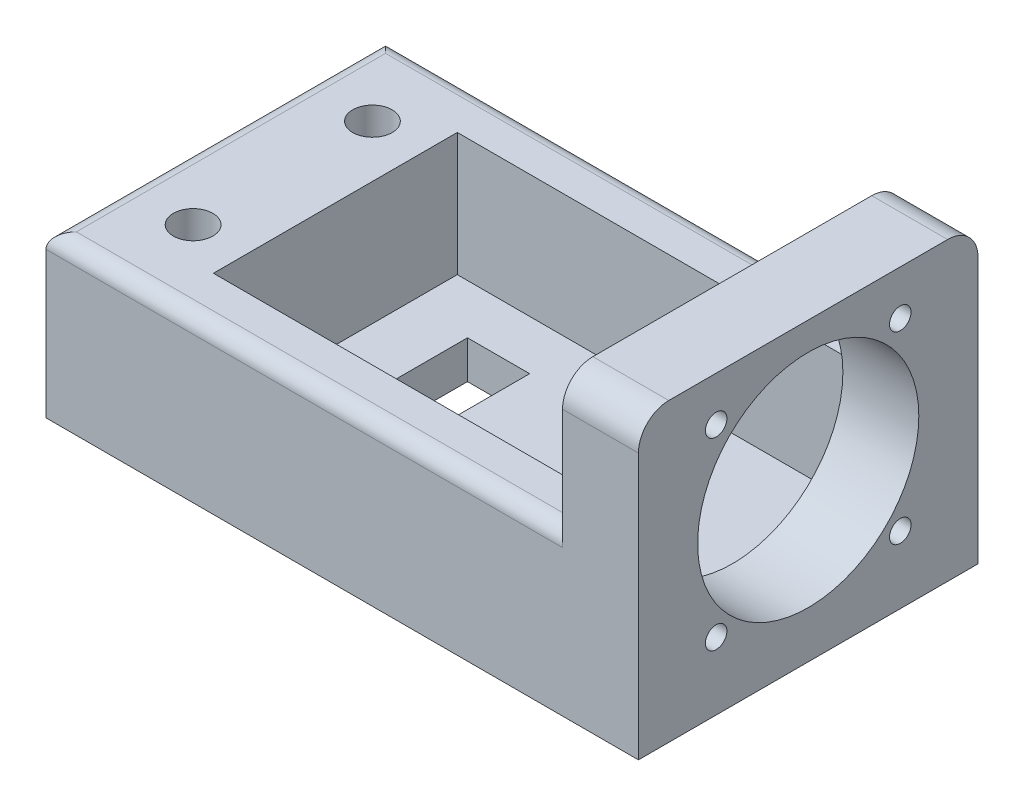
SolidWorks part; units mm, degrees
material "ABS PC"
ref_plane "Front Plane" through (0, 0, 0) normal (0, 0, 1) x (1, 0, 0)
ref_plane "Top Plane" through (0, 0, 0) normal (0, 1, 0) x (1, 0, 0)
ref_plane "Right Plane" through (0, 0, 0) normal (1, 0, 0) x (0, 0, -1)
sketch "Sketch1" plane through (0, 0, 0) normal (0, 1, 0) x (1, 0, 0)
  line L1 (0, 0) -> (43.2003, 0)
  line L2 (0, 0) -> (0, 28.3997)
  line L3 (0, 28.3997) -> (43.2003, 28.3997)
  line L4 (43.2003, 0) -> (43.2003, 28.3997)
  dimension "D1" = 28.3997
  dimension "D2" = 43.2003
extrude "Boss-Extrude1" add sketch "Sketch1" along normal blind 13.4747
sketch "Sketch2" plane through (0, 13.4747, 0) normal (0, 1, 0) x (1, 0, 0)
  line L0 (43.2003, 0) -> (43.2003, 28.3997) construction
  line L1 (43.2003, 24.3992) -> (10, 24.3992)
  line L2 (43.2003, 24.3992) -> (43.2003, 4.0005)
  line L3 (43.2003, 4.0005) -> (10, 4.0005)
  line L4 (10, 24.3992) -> (10, 4.0005)
  line L5 (0, 28.3997) -> (0, 0) construction
  line L6 (0, 0) -> (43.2003, 0) construction
  dimension "D1" = 10
  dimension "D2" = 20.3987
  dimension "D3" = 4.0005
extrude "Cut-Extrude1" cut sketch "Sketch2" against normal blind 10.2997
sketch "Sketch3" plane through (0, 3.175, 0) normal (0, 1, 0) x (1, 0, 0)
  line L1 (15.0012, 20.2502) -> (20.2006, 20.2501)
  line L2 (15.0012, 20.2502) -> (15.0012, 8.1496)
  line L3 (15.0012, 8.1496) -> (20.2006, 8.1496)
  line L4 (20.2006, 20.2501) -> (20.2006, 8.1496)
  line L5 (10, 24.3992) -> (10, 4.0005) construction
  line L6 (10, 4.0005) -> (43.2003, 4.0005) construction
  dimension "D1" = 12.1006
  dimension "D2" = 5.1994
  dimension "D3" = 5.0013
  dimension "D4" = 4.1491
extrude "Cut-Extrude2" cut sketch "Sketch3" against normal through all
sketch "Sketch4" plane through (43.2003, 0, 0) normal (1, 0, 0) x (0, 0, -1)
  line L8 (24.3992, 3.175) -> (4.0005, 3.175)
  line L9 (4.0005, 3.175) -> (4.0005, 13.4747)
  line L10 (4.0005, 13.4747) -> (0, 13.4747)
  line L11 (0, 13.4747) -> (0, 0)
  line L12 (0, 0) -> (28.3997, 0)
  line L13 (28.3997, 0) -> (28.3997, 13.4747)
  line L14 (28.3997, 13.4747) -> (24.3992, 13.4747)
  line L15 (24.3992, 13.4747) -> (24.3992, 3.175)
  line L16 (24.3992, 3.175) -> (4.0005, 3.175)
  line L17 (4.0005, 3.175) -> (4.0005, 13.4747)
  line L18 (4.0005, 13.4747) -> (0, 13.4747)
  line L19 (0, 13.4747) -> (0, 0)
  line L20 (0, 0) -> (28.3997, 0)
  line L21 (28.3997, 0) -> (28.3997, 13.4747)
  line L22 (28.3997, 13.4747) -> (24.3992, 13.4747)
  line L23 (24.3992, 13.4747) -> (24.3992, 3.175)
  dimension "D1" = 0
extrude "Boss-Extrude2" add sketch "Sketch4" along normal blind 6.35
sketch "Sketch5" plane through (0, 3.175, 0) normal (0, 1, 0) x (1, 0, 0)
  line L0 (49.5503, 28.3997) -> (0, 28.3997) construction
  line L1 (43.2003, 28.3997) -> (49.5503, 28.3997)
  line L2 (43.2003, 28.3997) -> (43.2003, 0)
  line L3 (43.2003, 0) -> (49.5503, 0)
  line L4 (10, 4.0005) -> (49.5503, 4.0005)
  line L5 (49.5503, 4.0005) -> (49.5503, 24.3992)
  line L6 (49.5503, 24.3992) -> (10, 24.3992)
  line L7 (10, 24.3992) -> (10, 4.0005)
  line L8 (10, 4.0005) -> (49.5503, 4.0005)
  line L9 (49.5503, 4.0005) -> (49.5503, 24.3992)
  line L10 (49.5503, 24.3992) -> (10, 24.3992)
  line L11 (10, 24.3992) -> (10, 4.0005)
  line L12 (49.5503, 28.3997) -> (49.5503, 0)
  dimension "D2" = 6.35
  dimension "D1" = 0
extrude "Boss-Extrude3" add sketch "Sketch5" along normal blind 21.59 contours L2 L1 L12 L3
sketch "Sketch6" plane through (49.5503, 0, 0) normal (1, 0, 0) x (0, 0, -1)
  line L0 (0, 3.068) -> (28.3997, 3.068) construction
  line L1 (0, 24.765) -> (0, 0) construction
  line L2 (28.3997, 0) -> (28.3997, 24.765) construction
  line L3 (0, 0) -> (28.3997, 0) construction
  circle A0 centre (14.1999, 13.177) radius 9.25
  point P10 (14.1999, 3.068)
  dimension "D2" = 18.5
  dimension "D1" = 3.068
  dimension "D3" = 10.109
extrude "Cut-Extrude3" cut sketch "Sketch6" against normal blind 25.4
sketch "Sketch7" plane through (49.5503, 0, 0) normal (1, 0, 0) x (0, 0, -1)
  line L0 (14.1999, 13.177) -> (14.1999, 22.427) construction
  line L1 (6.4999, 5.639) -> (21.8999, 5.639)
  line L2 (6.4999, 5.639) -> (6.4999, 21.039)
  line L7 (6.4999, 21.039) -> (21.8999, 21.039)
  line L12 (21.8999, 5.639) -> (21.8999, 21.039)
  line L13 (6.4999, 5.639) -> (21.8999, 21.039) construction
  line L14 (6.4999, 21.039) -> (21.8999, 5.639) construction
  circle A5 centre (6.4999, 21.039) radius 0.9
  circle A6 centre (21.8999, 21.039) radius 0.9
  circle A7 centre (21.8999, 5.639) radius 0.9
  circle A8 centre (6.4999, 5.639) radius 0.9
  circle A9 centre (14.1999, 13.177) radius 9.25 construction
  point P0 (14.1999, 13.339)
  dimension "D2" = 15.4
  dimension "D3" = 1.8
  dimension "D4" = 0.162
  dimension "D1" = 15.4
extrude "Cut-Extrude4" cut sketch "Sketch7" against normal blind 25.4 contours A5 | A6 | A7 | A8
fillet "Fillet1" radius 2.54 2 edges at (46.3753, 24.765, -28.3997) (46.3753, 24.765, 0)
fillet "Fillet2" radius 1.27 3 edges at (21.6002, 13.4747, 0) (21.6002, 13.4747, -28.3997) (0, 13.4747, -14.1999)
sketch "Sketch8" plane through (0, 13.4747, 0) normal (0, 1, 0) x (1, 0, 0)
  line L1 (1.27, 24.3992) -> (10, 24.3992) construction
  line L2 (1.27, 27.1297) -> (1.27, 1.27) construction
  line L3 (10, 24.3992) -> (10, 4.0005) construction
  line L4 (10, 4.0005) -> (1.27, 4.0005) construction
  line L5 (5.635, 24.3992) -> (5.635, 4.0005) construction
  circle A0 centre (5.635, 21.6675) radius 1.651
  circle A1 centre (5.635, 6.6675) radius 1.651
  dimension "D1" = 3.302
  dimension "D2" = 15
  dimension "D3" = 2.667
extrude "Cut-Extrude5" cut sketch "Sketch8" against normal blind 25.4
